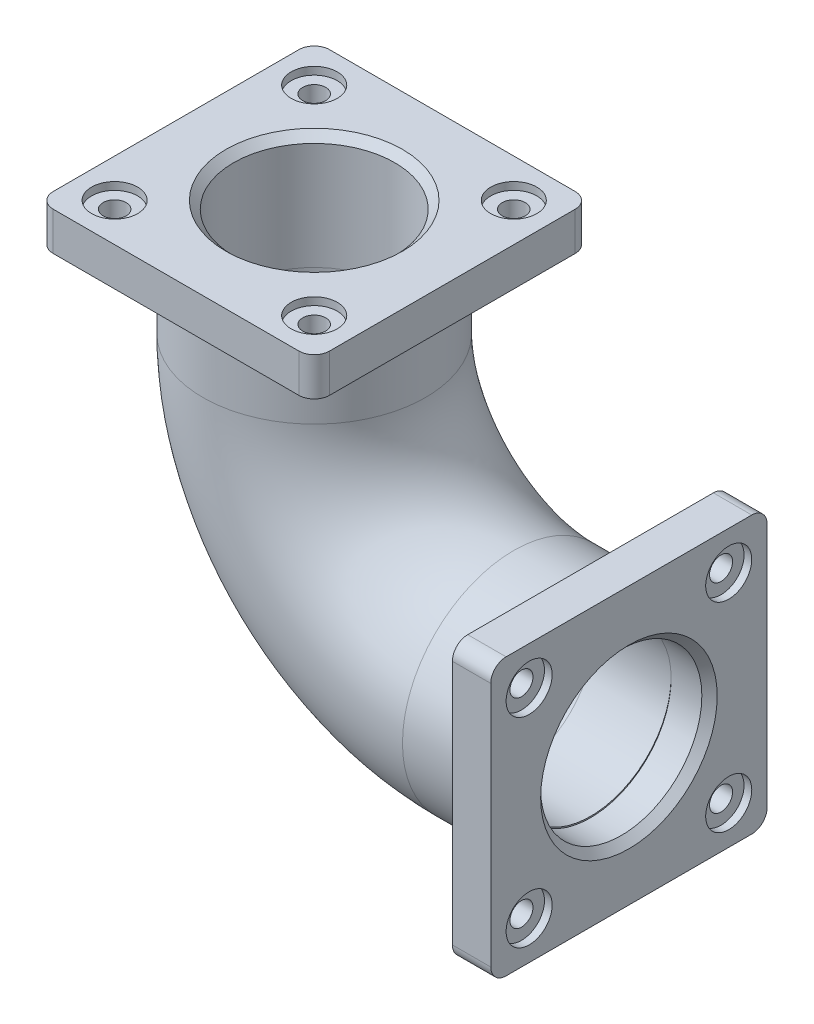
SolidWorks part; units mm, degrees
material "AISI 1020"
ref_plane "Front Plane" through (0, 0, 0) normal (0, 0, 1) x (1, 0, 0)
ref_plane "Top Plane" through (0, 0, 0) normal (0, 1, 0) x (1, 0, 0)
ref_plane "Right Plane" through (0, 0, 0) normal (1, 0, 0) x (0, 0, -1)
sketch "Sketch2" plane through (0, 0, 0) normal (0, 1, 0) x (1, 0, 0)
  circle A0 centre (0, 0) radius 145
  circle A1 centre (0, 0) radius 105
  dimension "D1" = 210
  dimension "D2" = 290
sketch "Sketch4" plane through (0, 0, 0) normal (0, 0, 1) x (1, 0, 0)
  line L0 (0, 0) -> (0, -150)
  line L1 (260, -410) -> (410, -410)
  arc A0 (0, -150) -> (260, -410) centre (260, -150) ccw
  dimension "D3" = 260
  dimension "D1" = 150
  dimension "D2" = 150
sweep "Sweep1" add profiles "Sketch2" path "Sketch4"
sketch "Sketch6" plane through (0, 0, 0) normal (0, 1, 0) x (1, 0, 0)
  line L1 (-160, 180) -> (160, 180)
  line L2 (-180, 160) -> (-180, -160)
  line L3 (-160, -180) -> (160, -180)
  line L4 (180, 160) -> (180, -160)
  line L5 (-180, 180) -> (180, -180) construction
  line L6 (-180, -180) -> (180, 180) construction
  line L7 (-130, 130) -> (130, 130) construction
  line L8 (-130, 130) -> (-130, -130) construction
  line L9 (-130, -130) -> (130, -130) construction
  line L10 (130, 130) -> (130, -130) construction
  line L11 (-130, 130) -> (130, -130) construction
  line L12 (-130, -130) -> (130, 130) construction
  circle A0 centre (-130, 130) radius 15
  circle A2 centre (130, 130) radius 15
  circle A3 centre (130, -130) radius 15
  circle A4 centre (-130, -130) radius 15
  arc A5 (-180, -160) -> (-160, -180) centre (-160, -160) ccw
  arc A6 (160, -180) -> (180, -160) centre (160, -160) ccw
  arc A7 (160, 180) -> (180, 160) centre (160, 160) cw
  arc A8 (-160, 180) -> (-180, 160) centre (-160, 160) ccw
  point P0 (0, 0)
  point P6 (0, 0)
  dimension "D4" = 30
  dimension "D5" = 20
  dimension "D1" = 360
  dimension "D2" = 360
  dimension "D3" = 260
extrude "Boss-Extrude1" add sketch "Sketch6" against normal blind 50
sketch "Sketch7" plane through (0, -50, 0) normal (0, -1, 0) x (-1, 0, 0)
  circle A0 centre (0, 0) radius 105
  dimension "D1" = 210
extrude "Cut-Extrude1" cut sketch "Sketch7" against normal blind 50
sketch "Sketch9" plane through (410, 0, 0) normal (1, 0, 0) x (0, 0, -1)
  line L1 (-180, -230) -> (180, -230)
  line L2 (-180, -230) -> (-180, -590)
  line L3 (-180, -590) -> (180, -590)
  line L4 (180, -230) -> (180, -590)
  line L5 (-180, -230) -> (180, -590) construction
  line L6 (-180, -590) -> (180, -230) construction
  line L7 (-130, -280) -> (130, -280) construction
  line L8 (-130, -280) -> (-130, -540) construction
  line L9 (-130, -540) -> (130, -540) construction
  line L10 (130, -280) -> (130, -540) construction
  line L11 (-130, -280) -> (130, -540) construction
  line L12 (-130, -540) -> (130, -280) construction
  circle A0 centre (-130, -280) radius 15
  circle A1 centre (-130, -540) radius 15
  circle A2 centre (130, -540) radius 15
  circle A3 centre (130, -280) radius 15
  point P0 (0, -410)
  point P6 (0, -410)
  dimension "D5" = 30
  dimension "D1" = 360
  dimension "D2" = 360
  dimension "D3" = 260
  dimension "D4" = 260
extrude "Boss-Extrude3" add sketch "Sketch9" against normal blind 50
sketch "Sketch10" plane through (0, 0, 0) normal (0, 1, 0) x (1, 0, 0)
  circle A0 centre (-130, 130) radius 30
  circle A1 centre (130, 130) radius 30
  circle A2 centre (130, -130) radius 30
  circle A3 centre (-130, -130) radius 30
  dimension "D1" = 60
extrude "Cut-Extrude3" cut sketch "Sketch10" against normal blind 10
sketch "Sketch11" plane through (410, 0, 0) normal (1, 0, 0) x (0, 0, -1)
  circle A0 centre (-130, -280) radius 30
  circle A1 centre (130, -280) radius 30
  circle A2 centre (-130, -540) radius 30
  circle A3 centre (130, -540) radius 30
  dimension "D1" = 60
extrude "Cut-Extrude4" cut sketch "Sketch11" against normal blind 10
fillet "Fillet2" radius 20 4 edges at (385, -590, -180) (385, -590, 180) (385, -230, -180) (385, -230, 180)
fillet "Fillet3" radius 10 2 edges at (0, -50, 145) (360, -410, -145)
sketch "Sketch12" plane through (410, 0, 0) normal (1, 0, 0) x (0, 0, -1)
  circle A0 centre (0, -411.6494) radius 105
  dimension "D1" = 210
extrude "Cut-Extrude5" cut sketch "Sketch12" against normal blind 50
chamfer "Chamfer2" distance 10 angle 45 2 edges at (0, 0, -105) (410, -411.6494, -105)
